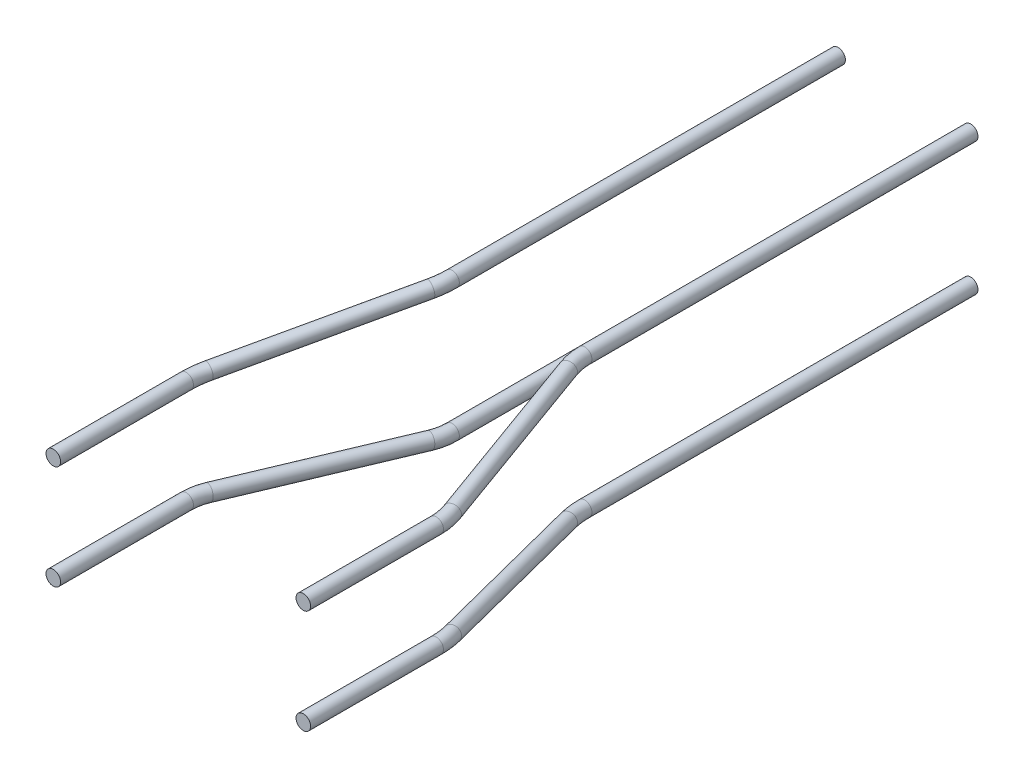
SolidWorks part; units mm, degrees
material "PVC Rigid"
ref_plane "Front Plane" through (0, 0, 0) normal (0, 0, 1) x (1, 0, 0)
ref_plane "Top Plane" through (0, 0, 0) normal (0, 1, 0) x (1, 0, 0)
ref_plane "Right Plane" through (0, 0, 0) normal (1, 0, 0) x (0, 0, -1)
sketch3d "Pipe path 1"
  line L0 (271.8198, 31.8198, -40) -> (271.8198, 31.8198, 145.287)
  line L1 (273.2244, 31.4799, 154.486) -> (298.5954, 25.3399, 235.514)
  line L2 (300, 25, 244.713) -> (300, 25, 308.5)
  arc A0 (271.8198, 31.8198, 145.287) -> (273.2244, 31.4799, 154.486) centre (300.9781, 24.7633, 145.287) ccw
  arc A1 (298.5954, 25.3399, 235.514) -> (300, 25, 244.713) centre (270.8417, 32.0565, 244.713) ccw
  point P6 (271.8198, 31.8198, 150)
  point P7 (308.0346, 53.9216, 145.287)
  point P10 (300, 25, 240)
  point P11 (263.7852, 2.8982, 244.713)
  dimension "D1" = 30
  dimension "D2" = 30
sweep "Pipe 1" add path "Pipe path 1" circular profile diameter 7 parameters "D3"=7
sketch3d "Pipe path 2"
  line L0 (208.1802, 31.8198, -40) -> (208.1802, 31.8198, 145.287)
  line L1 (206.7756, 31.4799, 154.486) -> (181.4046, 25.3399, 235.514)
  line L2 (180, 25, 244.713) -> (180, 25, 308.5)
  arc A0 (208.1802, 31.8198, 145.287) -> (206.7756, 31.4799, 154.486) centre (179.0219, 24.7633, 145.287) ccw
  arc A1 (181.4046, 25.3399, 235.514) -> (180, 25, 244.713) centre (209.1583, 32.0565, 244.713) ccw
  point P6 (208.1802, 31.8198, 150)
  point P7 (186.0784, -4.395, 145.287)
  point P10 (180, 25, 240)
  point P11 (202.1018, 61.2148, 244.713)
  dimension "D1" = 30
  dimension "D2" = 30
sweep "Pipe 2" add path "Pipe path 2" circular profile diameter 7 parameters "D3"=7
sketch3d "Pipe path 3"
  line L0 (208.1802, -31.8198, -40) -> (208.1802, -31.8198, 145.287)
  line L1 (206.7756, -31.4799, 154.486) -> (181.4046, -25.3399, 235.514)
  line L2 (180, -25, 244.713) -> (180, -25, 308.5)
  arc A0 (208.1802, -31.8198, 145.287) -> (206.7756, -31.4799, 154.486) centre (179.0219, -24.7633, 145.287) ccw
  arc A1 (181.4046, -25.3399, 235.514) -> (180, -25, 244.713) centre (209.1583, -32.0565, 244.713) ccw
  point P6 (208.1802, -31.8198, 150)
  point P7 (171.9654, -53.9216, 145.287)
  point P10 (180, -25, 240)
  point P11 (216.2148, -2.8982, 244.713)
  dimension "D1" = 30
  dimension "D2" = 30
sweep "Pipe 3" add path "Pipe path 3" circular profile diameter 7 parameters "D3"=7
sketch3d "Pipe path 4"
  line L0 (271.8198, -31.8198, -40) -> (271.8198, -31.8198, 145.287)
  line L1 (273.2244, -31.4799, 154.486) -> (298.5954, -25.3399, 235.514)
  line L2 (300, -25, 244.713) -> (300, -25, 308.5)
  arc A0 (271.8198, -31.8198, 145.287) -> (273.2244, -31.4799, 154.486) centre (300.9781, -24.7633, 145.287) ccw
  arc A1 (298.5954, -25.3399, 235.514) -> (300, -25, 244.713) centre (270.8417, -32.0565, 244.713) ccw
  point P6 (271.8198, -31.8198, 150)
  point P7 (293.9216, 4.395, 145.287)
  point P10 (300, -25, 240)
  point P11 (277.8982, -61.2148, 244.713)
  dimension "D1" = 30
  dimension "D2" = 30
sweep "Pipe 4" add path "Pipe path 4" circular profile diameter 7 parameters "D3"=7
